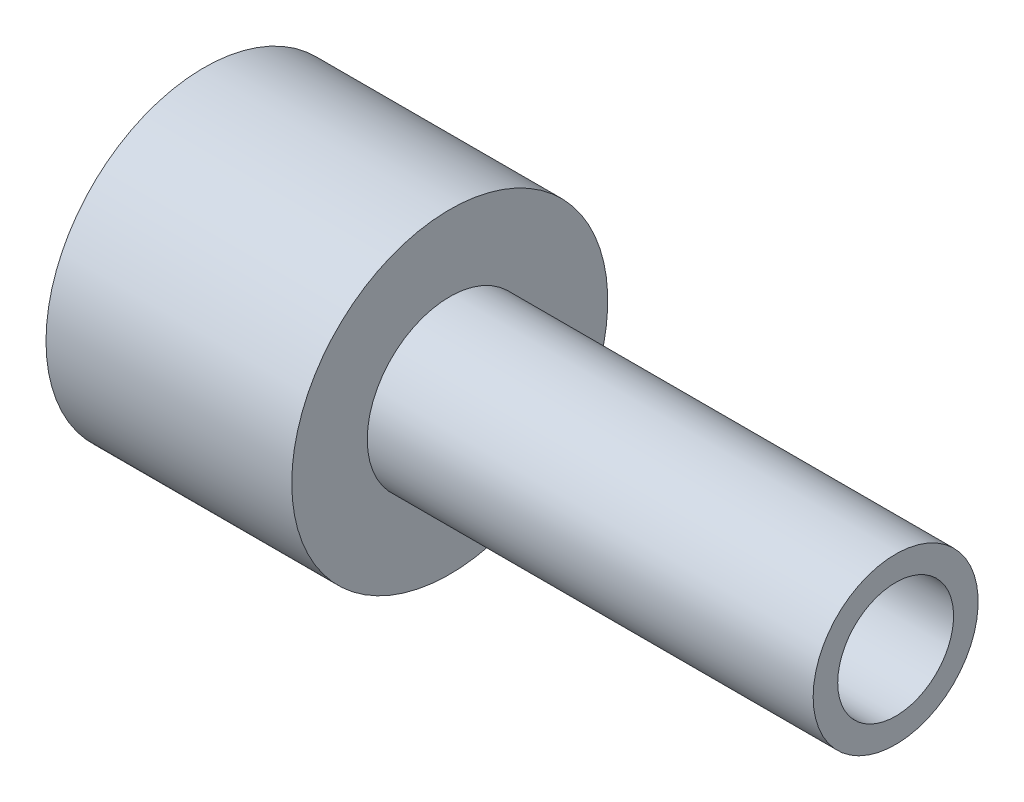
SolidWorks part; units mm, degrees
ref_plane "Front Plane" through (0, 0, 0) normal (0, 0, 1) x (1, 0, 0)
ref_plane "Top Plane" through (0, 0, 0) normal (0, 1, 0) x (1, 0, 0)
ref_plane "Right Plane" through (0, 0, 0) normal (1, 0, 0) x (0, 0, -1)
sketch "Axial profile (mm)" plane through (0, 0, 0) normal (0, 0, 1) x (1, 0, 0)
  line L0 (-110, 0) -> (75, 0) construction
  line L1 (-6, 1.65) -> (13.7, 1.65)
  line L2 (13.7, 1.65) -> (13.7, 2.35)
  line L3 (13.7, 2.35) -> (1, 2.35)
  line L4 (1, 2.35) -> (1, 4.5)
  line L5 (1, 4.5) -> (-6, 4.5)
  line L6 (-6, 4.5) -> (-6, 1.65)
revolve "Full revolution" add sketch "Axial profile (mm)" angle 360 about L0
